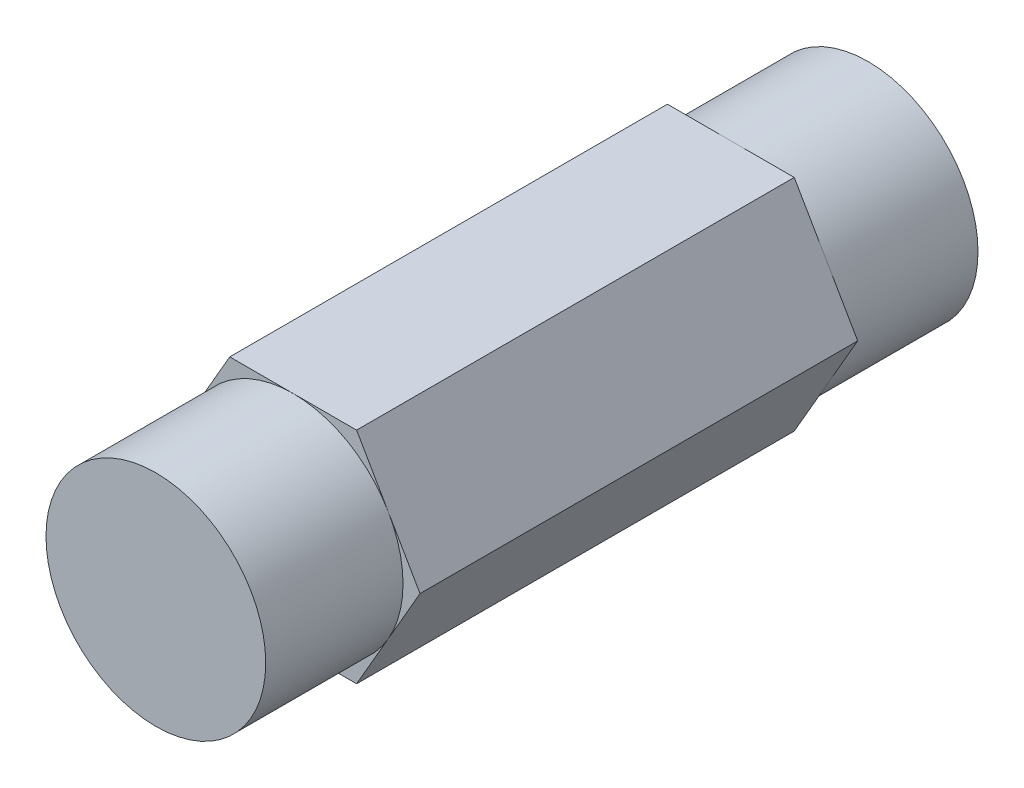
SolidWorks part; units mm, degrees
ref_plane "Front Plane" through (0, 0, 0) normal (0, 0, 1) x (1, 0, 0)
ref_plane "Top Plane" through (0, 0, 0) normal (0, 1, 0) x (1, 0, 0)
ref_plane "Right Plane" through (0, 0, 0) normal (1, 0, 0) x (0, 0, -1)
sketch "Sketch1" plane through (0, 0, 0) normal (0, 0, 1) x (1, 0, 0)
  circle A0 centre (0, 0) radius 6.35
  dimension "D1" = 12.7
extrude "Boss-Extrude1" add sketch "Sketch1" along normal blind 7.9375
sketch "Sketch2" plane through (0, 0, 7.9375) normal (0, 0, 1) x (1, 0, 0)
  line L1 (7.3323, 0) -> (3.6662, 6.35)
  line L2 (3.6662, 6.35) -> (-3.6662, 6.35)
  line L3 (-3.6662, 6.35) -> (-7.3323, 0)
  line L4 (-7.3323, 0) -> (-3.6662, -6.35)
  line L5 (-3.6662, -6.35) -> (3.6662, -6.35)
  line L6 (3.6662, -6.35) -> (7.3323, 0)
  circle A0 centre (0, 0) radius 6.35 construction
  dimension "D1" = 12.7
extrude "Boss-Extrude2" add sketch "Sketch2" along normal blind 25.2984
sketch "Sketch3" plane through (0, 0, 33.2359) normal (0, 0, 1) x (1, 0, 0)
  circle A0 centre (0, 0) radius 6.35
  dimension "D1" = 12.7
extrude "Boss-Extrude3" add sketch "Sketch3" along normal blind 7.9375
